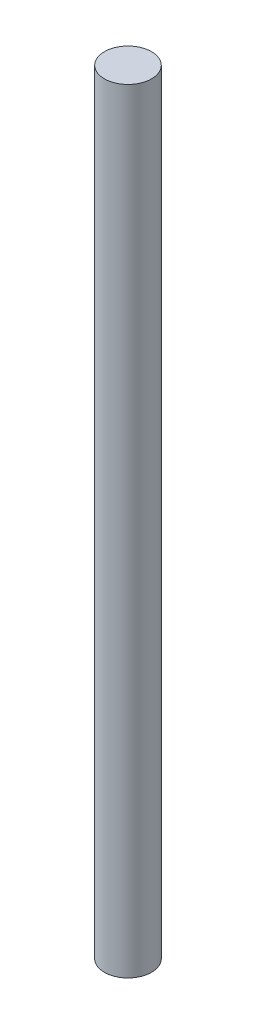
SolidWorks part; units mm, degrees
ref_plane "Front Plane" through (0, 0, 0) normal (0, 0, 1) x (1, 0, 0)
ref_plane "Top Plane" through (0, 0, 0) normal (0, 1, 0) x (1, 0, 0)
ref_plane "Right Plane" through (0, 0, 0) normal (1, 0, 0) x (0, 0, -1)
sketch "Sketch1" plane through (0, 0, 0) normal (0, 1, 0) x (1, 0, 0)
  circle A0 centre (0, 0) radius 5.0263
extrude "Boss-Extrude1" add sketch "Sketch1" along normal blind 165.1
